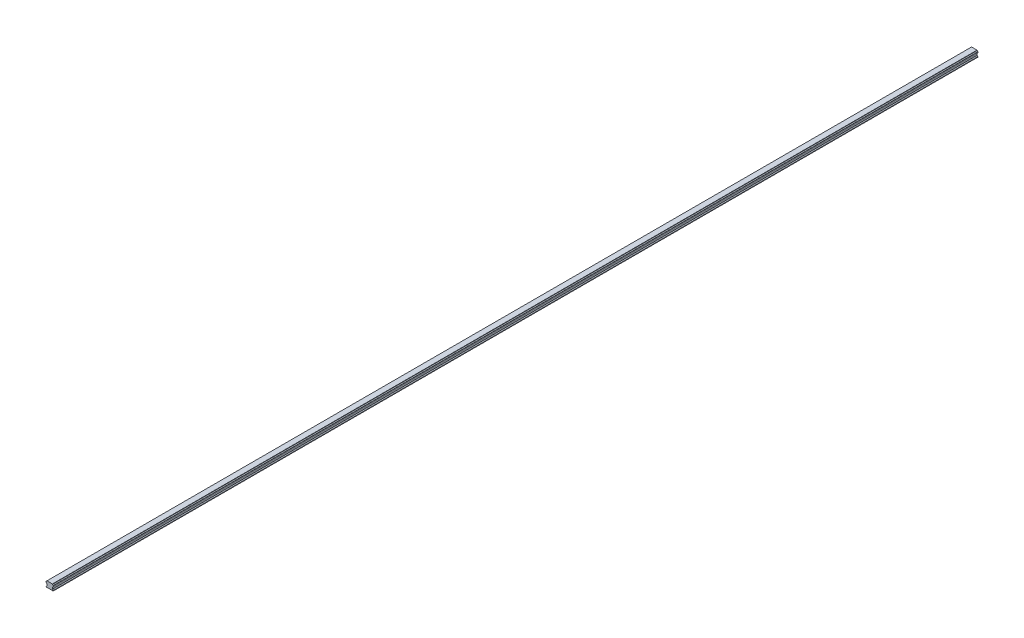
SolidWorks part; units mm, degrees
ref_plane "Piano frontale" through (0, 0, 0) normal (0, 0, 1) x (1, 0, 0)
ref_plane "Piano superiore" through (0, 0, 0) normal (0, 1, 0) x (1, 0, 0)
ref_plane "Piano destro" through (0, 0, 0) normal (1, 0, 0) x (0, 0, -1)
sketch "Schizzo1" plane through (0, 0, 0) normal (0, 0, 1) x (1, 0, 0)
  line L0 (-10.0871, -16.416) -> (-7.5656, -13.8945)
  line L1 (-7.5656, -13.8945) -> (-7.5656, -8.8516)
  line L2 (-7.5656, -8.8516) -> (-8.0776, -8.3396)
  line L3 (-10.3951, -6.0221) -> (-10.5914, -5.8258)
  line L4 (-10.5914, -5.8258) -> (-10.5914, -2.8001)
  line L5 (-10.5914, -2.8001) -> (-10.3951, -2.6038)
  line L6 (-8.0776, -0.2862) -> (-7.5656, 0.2257)
  line L7 (-7.5656, 0.2257) -> (9.5804, 0.2257)
  line L8 (9.5804, 0.2257) -> (10.0923, -0.2862)
  line L9 (12.4099, -2.6038) -> (12.6061, -2.8001)
  line L10 (12.6061, -2.8001) -> (12.6061, -5.8258)
  line L11 (12.6061, -5.8258) -> (12.4099, -6.0221)
  line L12 (10.0923, -8.3396) -> (9.5804, -8.8516)
  line L13 (9.5804, -8.8516) -> (9.5804, -13.8945)
  line L14 (9.5804, -13.8945) -> (12.1018, -16.416)
  line L16 (-10.0871, -16.416) -> (-10.0871, -17.7743)
  line L17 (-10.0871, -17.7743) -> (12.1018, -17.7743)
  line L18 (12.1018, -17.7743) -> (12.1018, -16.416)
  arc A0 (-8.0776, -8.3396) -> (-10.3951, -6.0221) centre (-10.5914, -8.5359) ccw
  arc A1 (-10.3951, -2.6038) -> (-8.0776, -0.2862) centre (-10.5914, -0.09) ccw
  arc A2 (10.0923, -0.2862) -> (12.4099, -2.6038) centre (12.6061, -0.09) ccw
  arc A3 (12.4099, -6.0221) -> (10.0923, -8.3396) centre (12.6061, -8.5359) ccw
  dimension "D1" = 18
extrude "Estrusione-Estrusione1" add sketch "Schizzo1" along normal blind 2900
